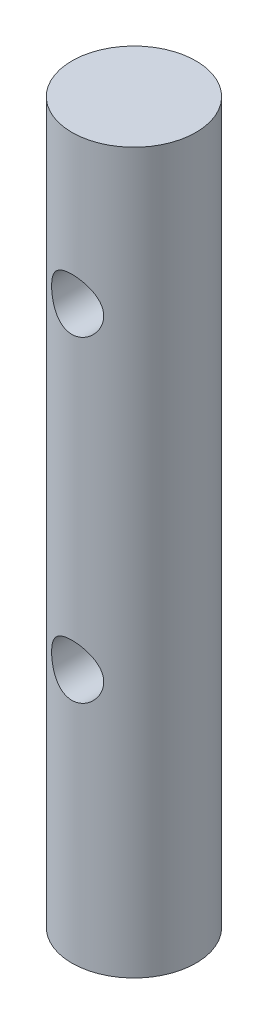
SolidWorks part; units mm, degrees
ref_plane "Front Plane" through (0, 0, 0) normal (0, 0, 1) x (1, 0, 0)
ref_plane "Top Plane" through (0, 0, 0) normal (0, 1, 0) x (1, 0, 0)
ref_plane "Right Plane" through (0, 0, 0) normal (1, 0, 0) x (0, 0, -1)
sketch "Sketch1" plane through (0, 0, 0) normal (0, 1, 0) x (1, 0, 0)
  circle A0 centre (0, 0) radius 5
  dimension "D1" = 10
extrude "Boss-Extrude1" add sketch "Sketch1" along normal blind 58
sketch "Sketch2" plane through (0, 0, 0) normal (0, 0, 1) x (1, 0, 0)
  line L0 (5, 58) -> (-5, 58) construction
  line L1 (5, 0) -> (5, 58) construction
  line L2 (-5, 58) -> (-5, 0) construction
  circle A0 centre (0, 46) radius 2.1
  circle A1 centre (0, 20.45) radius 2.1
  dimension "D2" = 4.2
  dimension "D4" = 4.2
  dimension "D1" = 12
  dimension "D3" = 5
  dimension "D5" = 20.45
  dimension "D6" = 5
extrude "Cut-Extrude1" cut sketch "Sketch2" against normal through all both and the other way through all
